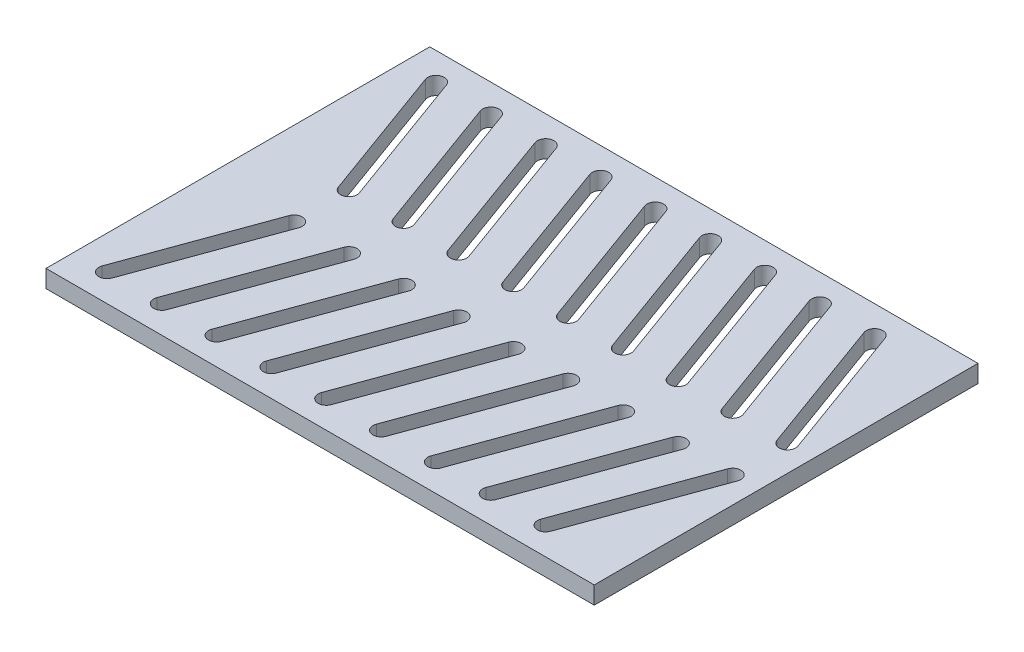
SolidWorks part; units mm, degrees
ref_plane "Спереди" through (0, 0, 0) normal (0, 0, 1) x (1, 0, 0)
ref_plane "Сверху" through (0, 0, 0) normal (0, 1, 0) x (1, 0, 0)
ref_plane "Справа" through (0, 0, 0) normal (1, 0, 0) x (0, 0, -1)
other "Configuration Table"
sketch "Эскиз1" plane through (0, 0, 0) normal (0, 1, 0) x (1, 0, 0)
  line L0 (-50, 0) -> (50, 0) construction
  line L1 (-50, -35) -> (50, -35)
  line L2 (-50, -35) -> (-50, 35)
  line L3 (-50, 35) -> (50, 35)
  line L4 (50, -35) -> (50, 35)
  line L5 (-50, -35) -> (50, 35) construction
  line L6 (-50, 35) -> (50, -35) construction
  line L7 (0, 35) -> (0, 0) construction
  line L8 (0, 30) -> (-50000, 30) construction
  line L9 (0, 5) -> (-50000, 5) construction
  line L10 (-43.8634, 30) -> (-34.7642, 5) construction
  line L11 (-42.4539, 30.513) -> (-33.3546, 5.513)
  line L12 (-45.2729, 29.487) -> (-36.1737, 4.487)
  line L13 (-33.8634, 30) -> (-24.7642, 5) construction
  line L14 (-32.4539, 30.513) -> (-23.3546, 5.513)
  line L15 (-35.2729, 29.487) -> (-26.1737, 4.487)
  line L16 (-23.8634, 30) -> (-14.7642, 5) construction
  line L17 (-22.4539, 30.513) -> (-13.3546, 5.513)
  line L18 (-25.2729, 29.487) -> (-16.1737, 4.487)
  line L19 (-13.8634, 30) -> (-4.7642, 5) construction
  line L20 (-12.4539, 30.513) -> (-3.3546, 5.513)
  line L21 (-15.2729, 29.487) -> (-6.1737, 4.487)
  line L22 (-3.8634, 30) -> (5.2358, 5) construction
  line L23 (-2.4539, 30.513) -> (6.6454, 5.513)
  line L24 (-5.2729, 29.487) -> (3.8263, 4.487)
  line L25 (6.1366, 30) -> (15.2358, 5) construction
  line L26 (7.5461, 30.513) -> (16.6454, 5.513)
  line L27 (4.7271, 29.487) -> (13.8263, 4.487)
  line L28 (16.1366, 30) -> (25.2358, 5) construction
  line L29 (17.5461, 30.513) -> (26.6454, 5.513)
  line L30 (14.7271, 29.487) -> (23.8263, 4.487)
  line L31 (26.1366, 30) -> (35.2358, 5) construction
  line L32 (27.5461, 30.513) -> (36.6454, 5.513)
  line L33 (24.7271, 29.487) -> (33.8263, 4.487)
  line L34 (36.1366, 30) -> (45.2358, 5) construction
  line L35 (37.5461, 30.513) -> (46.6454, 5.513)
  line L36 (34.7271, 29.487) -> (43.8263, 4.487)
  line L37 (-3.8634, -30) -> (5.2358, -5) construction
  line L38 (-2.4539, -30.513) -> (6.6454, -5.513)
  line L39 (-5.2729, -29.487) -> (3.8263, -4.487)
  line L40 (36.1366, -30) -> (45.2358, -5) construction
  line L41 (37.5461, -30.513) -> (46.6454, -5.513)
  line L42 (34.7271, -29.487) -> (43.8263, -4.487)
  line L43 (26.1366, -30) -> (35.2358, -5) construction
  line L44 (27.5461, -30.513) -> (36.6454, -5.513)
  line L45 (24.7271, -29.487) -> (33.8263, -4.487)
  line L46 (16.1366, -30) -> (25.2358, -5) construction
  line L47 (17.5461, -30.513) -> (26.6454, -5.513)
  line L48 (14.7271, -29.487) -> (23.8263, -4.487)
  line L49 (6.1366, -30) -> (15.2358, -5) construction
  line L50 (7.5461, -30.513) -> (16.6454, -5.513)
  line L51 (4.7271, -29.487) -> (13.8263, -4.487)
  line L52 (-13.8634, -30) -> (-4.7642, -5) construction
  line L53 (-12.4539, -30.513) -> (-3.3546, -5.513)
  line L54 (-15.2729, -29.487) -> (-6.1737, -4.487)
  line L55 (-23.8634, -30) -> (-14.7642, -5) construction
  line L56 (-22.4539, -30.513) -> (-13.3546, -5.513)
  line L57 (-25.2729, -29.487) -> (-16.1737, -4.487)
  line L58 (-33.8634, -30) -> (-24.7642, -5) construction
  line L59 (-32.4539, -30.513) -> (-23.3546, -5.513)
  line L60 (-35.2729, -29.487) -> (-26.1737, -4.487)
  line L61 (-43.8634, -30) -> (-34.7642, -5) construction
  line L62 (-42.4539, -30.513) -> (-33.3546, -5.513)
  line L63 (-45.2729, -29.487) -> (-36.1737, -4.487)
  arc A0 (-42.4539, 30.513) -> (-45.2729, 29.487) centre (-43.8634, 30) ccw
  arc A1 (-36.1737, 4.487) -> (-33.3546, 5.513) centre (-34.7642, 5) ccw
  arc A2 (-32.4539, 30.513) -> (-35.2729, 29.487) centre (-33.8634, 30) ccw
  arc A3 (-26.1737, 4.487) -> (-23.3546, 5.513) centre (-24.7642, 5) ccw
  arc A4 (-22.4539, 30.513) -> (-25.2729, 29.487) centre (-23.8634, 30) ccw
  arc A5 (-16.1737, 4.487) -> (-13.3546, 5.513) centre (-14.7642, 5) ccw
  arc A6 (-12.4539, 30.513) -> (-15.2729, 29.487) centre (-13.8634, 30) ccw
  arc A7 (-6.1737, 4.487) -> (-3.3546, 5.513) centre (-4.7642, 5) ccw
  arc A8 (-2.4539, 30.513) -> (-5.2729, 29.487) centre (-3.8634, 30) ccw
  arc A9 (3.8263, 4.487) -> (6.6454, 5.513) centre (5.2358, 5) ccw
  arc A10 (7.5461, 30.513) -> (4.7271, 29.487) centre (6.1366, 30) ccw
  arc A11 (13.8263, 4.487) -> (16.6454, 5.513) centre (15.2358, 5) ccw
  arc A12 (17.5461, 30.513) -> (14.7271, 29.487) centre (16.1366, 30) ccw
  arc A13 (23.8263, 4.487) -> (26.6454, 5.513) centre (25.2358, 5) ccw
  arc A14 (27.5461, 30.513) -> (24.7271, 29.487) centre (26.1366, 30) ccw
  arc A15 (33.8263, 4.487) -> (36.6454, 5.513) centre (35.2358, 5) ccw
  arc A16 (37.5461, 30.513) -> (34.7271, 29.487) centre (36.1366, 30) ccw
  arc A17 (43.8263, 4.487) -> (46.6454, 5.513) centre (45.2358, 5) ccw
  arc A18 (-2.4539, -30.513) -> (-5.2729, -29.487) centre (-3.8634, -30) cw
  arc A19 (3.8263, -4.487) -> (6.6454, -5.513) centre (5.2358, -5) cw
  arc A20 (37.5461, -30.513) -> (34.7271, -29.487) centre (36.1366, -30) cw
  arc A21 (43.8263, -4.487) -> (46.6454, -5.513) centre (45.2358, -5) cw
  arc A22 (27.5461, -30.513) -> (24.7271, -29.487) centre (26.1366, -30) cw
  arc A23 (33.8263, -4.487) -> (36.6454, -5.513) centre (35.2358, -5) cw
  arc A24 (17.5461, -30.513) -> (14.7271, -29.487) centre (16.1366, -30) cw
  arc A25 (23.8263, -4.487) -> (26.6454, -5.513) centre (25.2358, -5) cw
  arc A26 (7.5461, -30.513) -> (4.7271, -29.487) centre (6.1366, -30) cw
  arc A27 (13.8263, -4.487) -> (16.6454, -5.513) centre (15.2358, -5) cw
  arc A28 (-12.4539, -30.513) -> (-15.2729, -29.487) centre (-13.8634, -30) cw
  arc A29 (-6.1737, -4.487) -> (-3.3546, -5.513) centre (-4.7642, -5) cw
  arc A30 (-22.4539, -30.513) -> (-25.2729, -29.487) centre (-23.8634, -30) cw
  arc A31 (-16.1737, -4.487) -> (-13.3546, -5.513) centre (-14.7642, -5) cw
  arc A32 (-32.4539, -30.513) -> (-35.2729, -29.487) centre (-33.8634, -30) cw
  arc A33 (-26.1737, -4.487) -> (-23.3546, -5.513) centre (-24.7642, -5) cw
  arc A34 (-42.4539, -30.513) -> (-45.2729, -29.487) centre (-43.8634, -30) cw
  arc A35 (-36.1737, -4.487) -> (-33.3546, -5.513) centre (-34.7642, -5) cw
  point P0 (0, 0)
  point P16 (-39.3138, 17.5)
  point P25 (-29.3138, 17.5)
  point P32 (-19.3138, 17.5)
  point P39 (-9.3138, 17.5)
  point P46 (0.6862, 17.5)
  point P53 (10.6862, 17.5)
  point P60 (20.6862, 17.5)
  point P67 (30.6862, 17.5)
  point P74 (40.6862, 17.5)
  point P79 (0.6862, -17.5)
  point P86 (40.6862, -17.5)
  point P93 (30.6862, -17.5)
  point P100 (20.6862, -17.5)
  point P107 (10.6862, -17.5)
  point P114 (-9.3138, -17.5)
  point P121 (-19.3138, -17.5)
  point P128 (-29.3138, -17.5)
  point P135 (-39.3138, -17.5)
  dimension "D5" = 70
  dimension "D1" = 100
  dimension "D2" = 70
  dimension "D3" = 5
  dimension "D4" = 5
  dimension "D6" = 9
extrude "Бобышка-Вытянуть1" add sketch "Эскиз1" along normal blind 3.2
